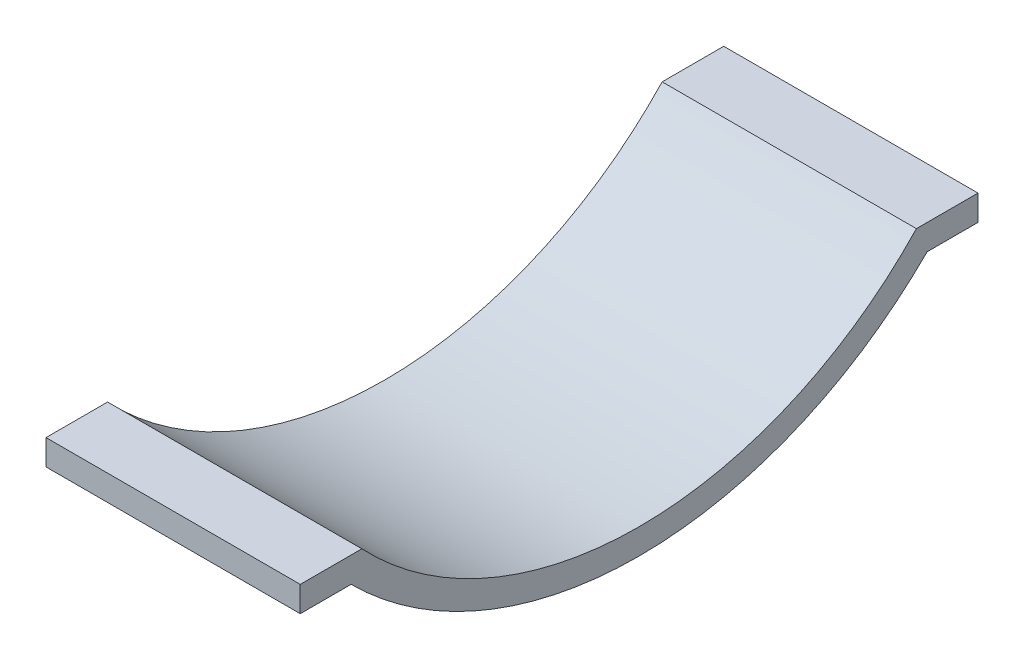
SolidWorks part; units mm, degrees
ref_plane "Plan de face" through (0, 0, 0) normal (0, 0, 1) x (1, 0, 0)
ref_plane "Plan de dessus" through (0, 0, 0) normal (0, 1, 0) x (1, 0, 0)
ref_plane "Plan de droite" through (0, 0, 0) normal (1, 0, 0) x (0, 0, -1)
sketch "Esquisse1" plane through (0, 0, 0) normal (1, 0, 0) x (0, 0, -1)
  line L2 (-89.8985, -36.4801) -> (-91.8985, -36.4801)
  line L3 (-91.8985, -36.4801) -> (-91.8985, -35.4801)
  line L4 (-91.8985, -35.4801) -> (-89.4756, -35.4801)
  line L5 (-67.2413, -36.4801) -> (-65.2413, -36.4801)
  line L6 (-65.2413, -36.4801) -> (-65.2413, -35.4801)
  line L7 (-65.2413, -35.4801) -> (-67.6642, -35.4801)
  arc A0 (-89.8985, -36.4801) -> (-67.2413, -36.4801) centre (-78.5699, -25.1812) ccw
  arc A1 (-89.4756, -35.4801) -> (-67.6642, -35.4801) centre (-78.5699, -25.1812) ccw
  dimension "D6" = 16
  dimension "D7" = 1
  dimension "D1" = 1
  dimension "D2" = 1
  dimension "D3" = 2
  dimension "D4" = 2
  dimension "D5" = 2.4229
extrude "Boss.-Extru.1" add sketch "Esquisse1" against normal blind 10
